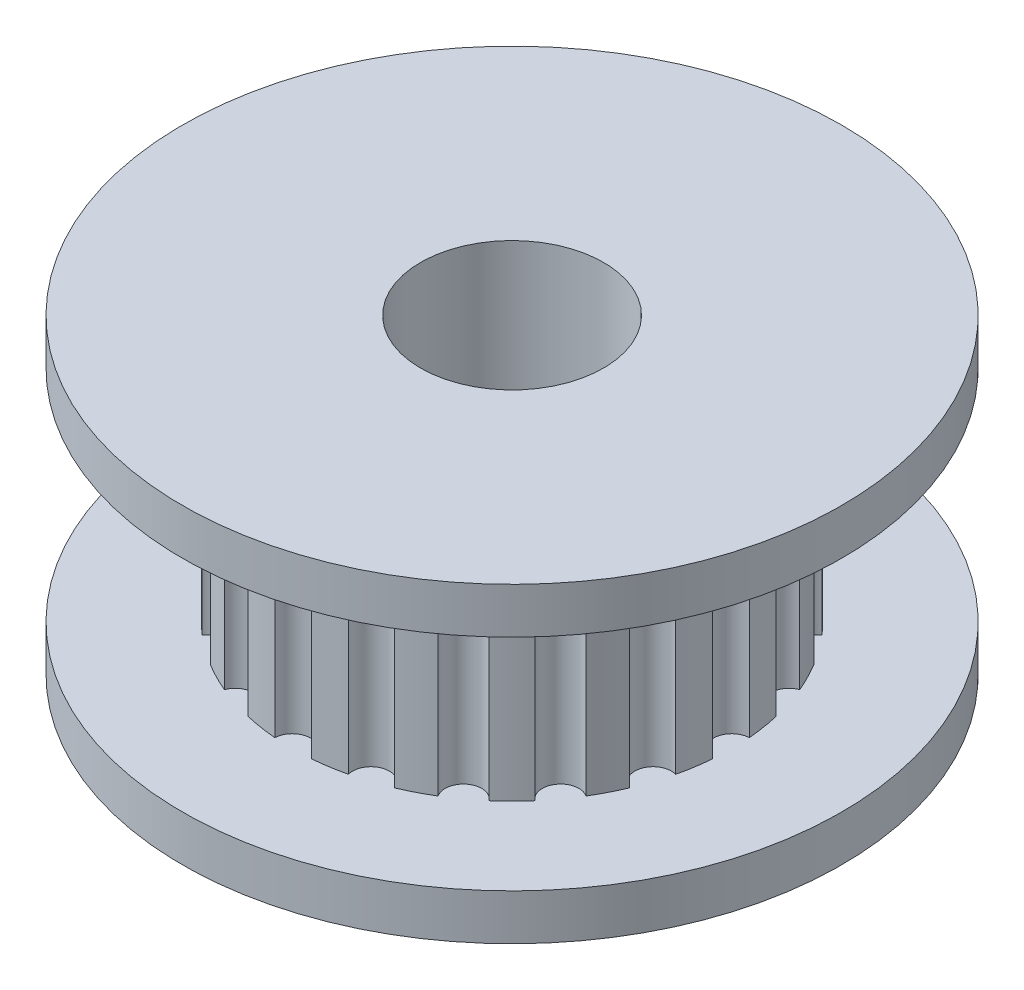
SolidWorks part; units mm, degrees
ref_plane "前视基准面" through (0, 0, 0) normal (0, 0, 1) x (1, 0, 0)
ref_plane "上视基准面" through (0, 0, 0) normal (0, 1, 0) x (1, 0, 0)
ref_plane "右视基准面" through (0, 0, 0) normal (1, 0, 0) x (0, 0, -1)
sketch "草图1" plane through (0, 0, 0) normal (0, 0, 1) x (1, 0, 0)
  line L0 (0, 0) -> (22.0862, 0) construction
  line L1 (0, 0) -> (0, 11.2679) construction
  line L2 (0, -8.5) -> (-9, -8.5)
  line L3 (-9, -8.5) -> (-9, -7.25)
  line L4 (-9, -7.25) -> (-6, -7.25)
  line L5 (-6, -7.25) -> (-6, -1.25)
  line L6 (-6, -1.25) -> (-9, -1.25)
  line L7 (-9, -1.25) -> (-9, 0)
  line L8 (-9, 0) -> (0, 0)
  line L9 (0, 0) -> (0, -8.5)
  dimension "D1" = 9
  dimension "D2" = 8.5
  dimension "D3" = 6
  dimension "D4" = 6
revolve "旋转1" add sketch "草图1" angle 360 about L1
sketch "草图2" plane through (0, 0, 0) normal (0, 1, 0) x (1, 0, 0)
  circle A0 centre (0, 0) radius 2.5
  dimension "D1" = 5
extrude "切除-拉伸1" cut sketch "草图2" against normal blind 10
sketch "草图5" plane through (0, -1.25, 0) normal (0, -1, 0) x (1, 0, 0)
  line L0 (-0.5, 6) -> (-0.5, 9.3117)
  line L1 (-0.5, 9.3117) -> (0.5, 9.3117)
  line L2 (0.5, 9.3117) -> (0.5, 6)
  circle A0 centre (0, 0) radius 6 construction
  circle A1 centre (0, 0) radius 6
  circle A2 centre (0, 6) radius 0.5
  circle M2 centre (0, 0) radius 9
  dimension "D1" = 1
extrude "切除-拉伸3" cut sketch "草图5" along normal blind 6 contours A2 L2 L0 M2
pattern_circular "阵列(圆周)2" count 20 over 360 about axis through (0, 0, 0) along (0, 1, 0) of "切除-拉伸3"
